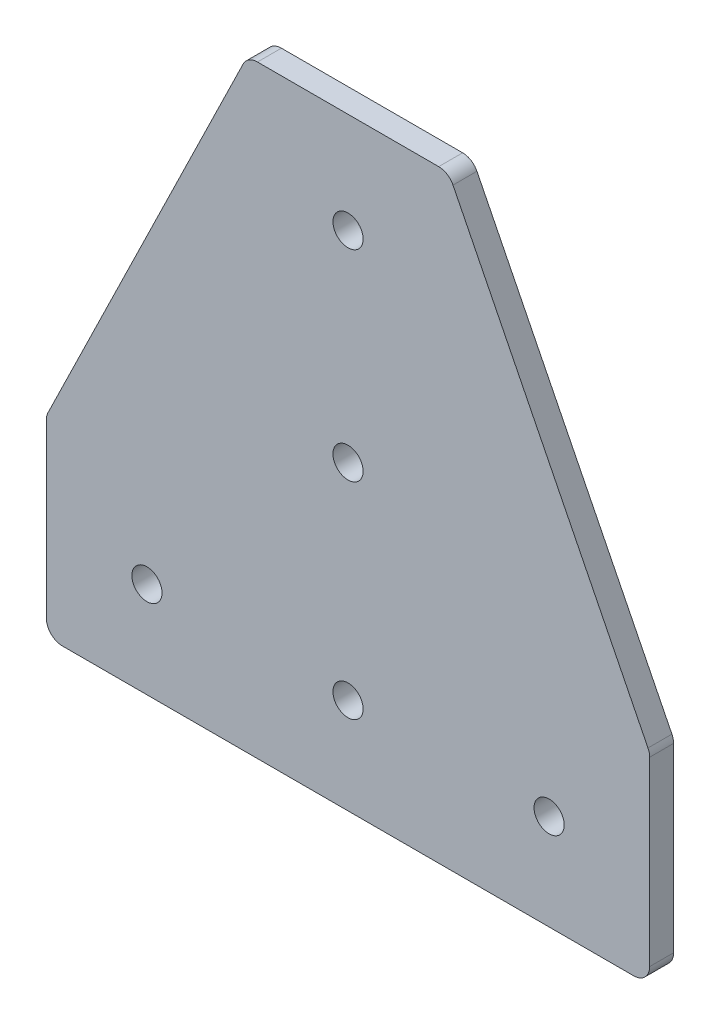
SolidWorks part; units mm, degrees
ref_plane "Front Plane" through (0, 0, 0) normal (0, 0, 1) x (1, 0, 0)
ref_plane "Top Plane" through (0, 0, 0) normal (0, 1, 0) x (1, 0, 0)
ref_plane "Right Plane" through (0, 0, 0) normal (1, 0, 0) x (0, 0, -1)
sketch "Sketch2" plane through (0, 0, 0) normal (0, 0, 1) x (1, 0, 0)
  line L0 (-31.1082, 42.6025) -> (8.8918, 124.5025)
  line L1 (-31.1082, 4.5025) -> (88.8918, 4.5025)
  line L2 (-31.1082, 4.5025) -> (-31.1082, 42.6025)
  line L4 (88.8918, 4.5025) -> (88.8918, 44.5025)
  line L5 (8.8918, 124.5025) -> (48.8918, 124.5025)
  line L6 (48.8918, 124.5025) -> (88.8918, 44.5025)
  circle A0 centre (28.8918, 104.5025) radius 3
  circle A1 centre (28.8918, 64.5025) radius 3
  circle A2 centre (-11.1082, 23.5525) radius 3
  circle A3 centre (68.8918, 23.5525) radius 3
  circle A4 centre (28.8918, 23.5525) radius 3
  dimension "D6" = 20
  dimension "D11" = 6
  dimension "D1" = 40
  dimension "D2" = 80
  dimension "D3" = 40
  dimension "D4" = 120
  dimension "D5" = 40
  dimension "D7" = 20
  dimension "D8" = 20
  dimension "D9" = 40
  dimension "D10" = 20
extrude "Boss-Extrude1" add sketch "Sketch2" along normal blind 4.7625
fillet "Fillet1" radius 3.18 6 edges at (88.8918, 4.5025, 2.3813) (-31.1082, 42.6025, 2.3813) (8.8918, 124.5025, 2.3813) (48.8918, 124.5025, 2.3813) (88.8918, 44.5025, 2.3813) (-31.1082, 4.5025, 2.3813)
